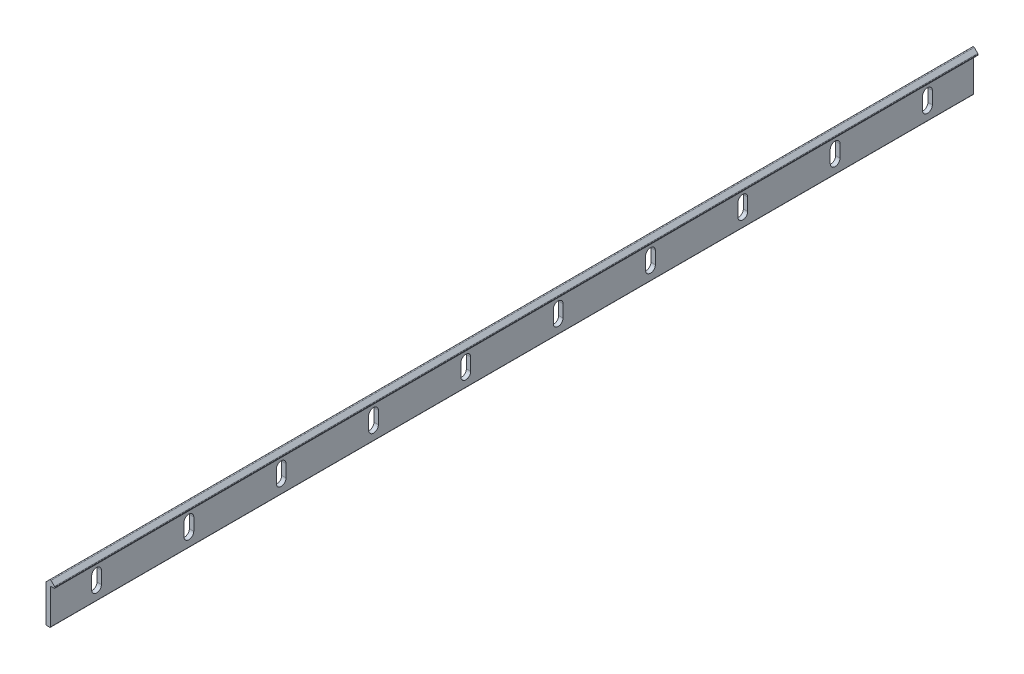
SolidWorks part; units mm, degrees
material "6061-T6 (SS)"
ref_plane "Front Plane" through (0, 0, 0) normal (0, 0, 1) x (1, 0, 0)
ref_plane "Top Plane" through (0, 0, 0) normal (0, 1, 0) x (1, 0, 0)
ref_plane "Right Plane" through (0, 0, 0) normal (1, 0, 0) x (0, 0, -1)
sketch "Sketch1" plane through (0, 0, 0) normal (0, 0, 1) x (1, 0, 0)
  line L0 (0, 20.3302) -> (2.0196, 22.3498)
  line L1 (0, 0) -> (2.375, 0)
  line L2 (0, 20.3302) -> (0, 0)
  line L4 (2.375, 0) -> (2.375, 19.5291)
  line L5 (2.375, 19.5291) -> (4.75, 19.5291)
  line L7 (2.7304, 22.3498) -> (4.75, 20.3302)
  line L8 (4.75, 19.5291) -> (4.75, 20.3302)
  arc A0 (2.7304, 22.3498) -> (2.0196, 22.3498) centre (2.375, 21.9944) ccw
  point P9 (2.375, 22.7052)
  dimension "D5" = 0.5026
  dimension "D6" = 22.497
  dimension "D1" = 2.375
  dimension "D2" = 19.5291
  dimension "D3" = 2.375
  dimension "D4" = 2.9679
extrude "Boss-Extrude1" add sketch "Sketch1" along normal blind 500
fillet "Fillet1" radius 0.5033 1 edges at (0, 20.3302, 250)
fillet "Fillet2" radius 0.504 1 edges at (4.75, 20.3302, 250)
fillet "Fillet3" radius 0.3016 1 edges at (4.75, 19.5291, 250)
fillet "Fillet4" radius 0.3016 2 edges at (0, 0, 250) (2.375, 0, 250)
sketch "Sketch2" plane through (0, 0, 0) normal (-1, 0, 0) x (0, 0, 1)
  line L0 (25, 13.1043) -> (25, 6.4043) construction
  line L1 (27.65, 13.1043) -> (27.65, 6.4043)
  line L2 (22.35, 13.1043) -> (22.35, 6.4043)
  line L3 (500, 0) -> (0, 0) construction
  line L4 (0, 20.1217) -> (0, 0.3016) construction
  arc A0 (27.65, 13.1043) -> (22.35, 13.1043) centre (25, 13.1043) ccw
  arc A1 (22.35, 6.4043) -> (27.65, 6.4043) centre (25, 6.4043) ccw
  point P2 (25, 9.7543)
  dimension "D3" = 9.7543
  dimension "D1" = 5.3
  dimension "D2" = 6.7
  dimension "D4" = 25
extrude "Cut-Extrude1" cut sketch "Sketch2" against normal up to next
pattern_linear "LPattern1" count 10 spacing 50 along (0, 0, 1) of "Cut-Extrude1"
equation "\"D3@Sketch1\"=\"D1@Sketch1\""
